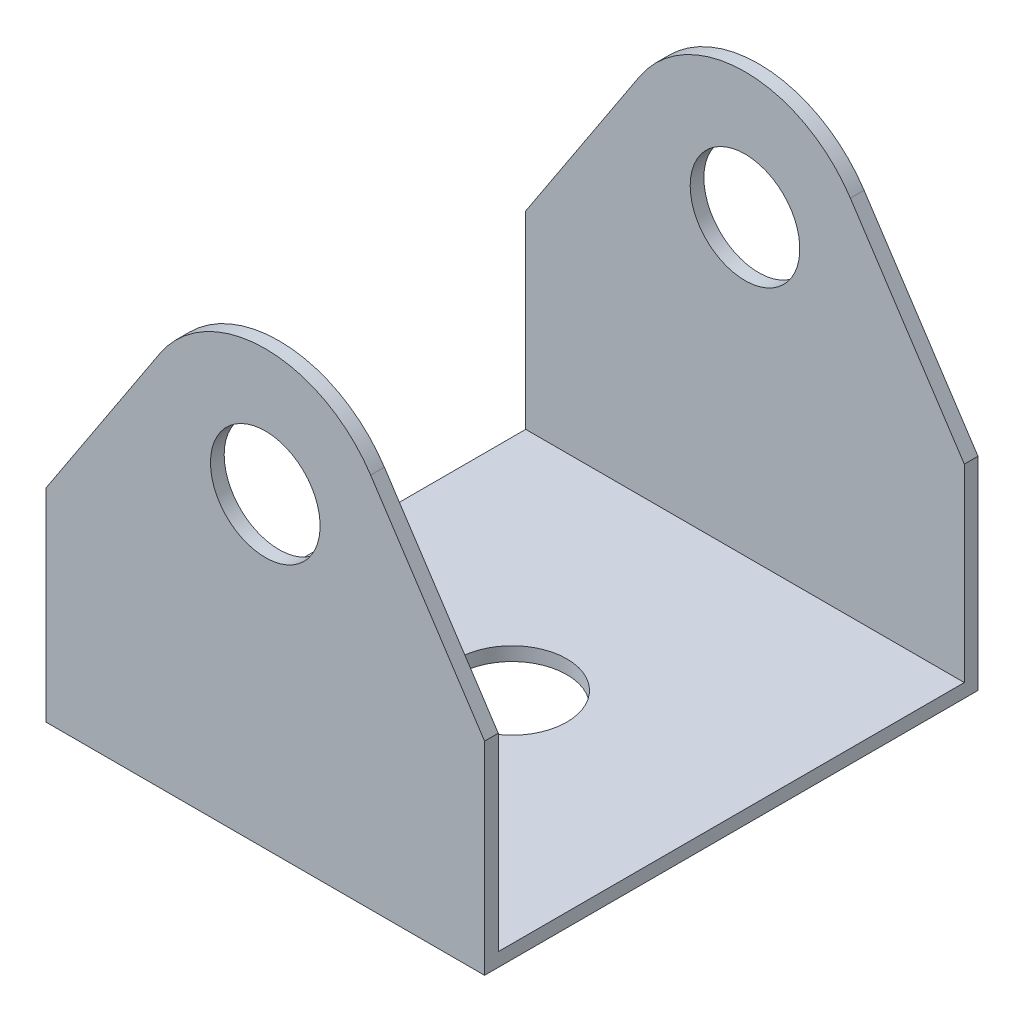
SolidWorks part; units mm, degrees
ref_plane "Plan de face" through (0, 0, 0) normal (0, 0, 1) x (1, 0, 0)
ref_plane "Plan de dessus" through (0, 0, 0) normal (0, 1, 0) x (1, 0, 0)
ref_plane "Plan de droite" through (0, 0, 0) normal (1, 0, 0) x (0, 0, -1)
sketch "Esquisse1" plane through (0, 0, 0) normal (0, 0, 1) x (1, 0, 0)
  line L0 (40, -56) -> (-40, -56)
  line L1 (-40, -19) -> (-40, -56)
  line L2 (0, 0) -> (0, -98.0836) construction
  line L3 (-40, -19) -> (-19.2233, 12.628)
  line L4 (0, 0) -> (0, 94.6013) construction
  line L5 (45.5595, 58.6907) -> (45.2694, 58.6907) construction
  line L6 (40, -19) -> (40, -56)
  line L7 (40, -19) -> (19.2233, 12.628)
  arc A0 (19.2233, 12.628) -> (-19.2233, 12.628) centre (0, 0) ccw
  point P11 (0, -56)
  dimension "D2" = 46
  dimension "D4" = 37
  dimension "D1" = 56
  dimension "D3" = 40
extrude "Extrusion1" add sketch "Esquisse1" along normal blind 90
shell "Coque1" thickness 2.5
sketch "Esquisse2" plane through (0, -56, 0) normal (0, -1, 0) x (1, 0, 0)
  line L0 (-40, 90) -> (-40, 0) construction
  line L1 (-40, 0) -> (40, 0) construction
  circle A0 centre (0, 45) radius 10
  dimension "D1" = 20
  dimension "D2" = 40
  dimension "D3" = 45
extrude "Enlèv. mat.-Extru.1" cut sketch "Esquisse2" against normal blind 90
sketch "Esquisse3" plane through (0, 0, 0) normal (0, 0, -1) x (-1, 0, 0)
  circle A0 centre (0, 0) radius 10
  arc A1 (19.2233, 12.628) -> (-19.2233, 12.628) centre (0, 0) ccw construction
  dimension "D1" = 20
extrude "Enlèv. mat.-Extru.2" cut sketch "Esquisse3" against normal through all
ref_plane "Plan1" through (0, 0, 45) normal (0, 0, 1) x (1, 0, 0)
